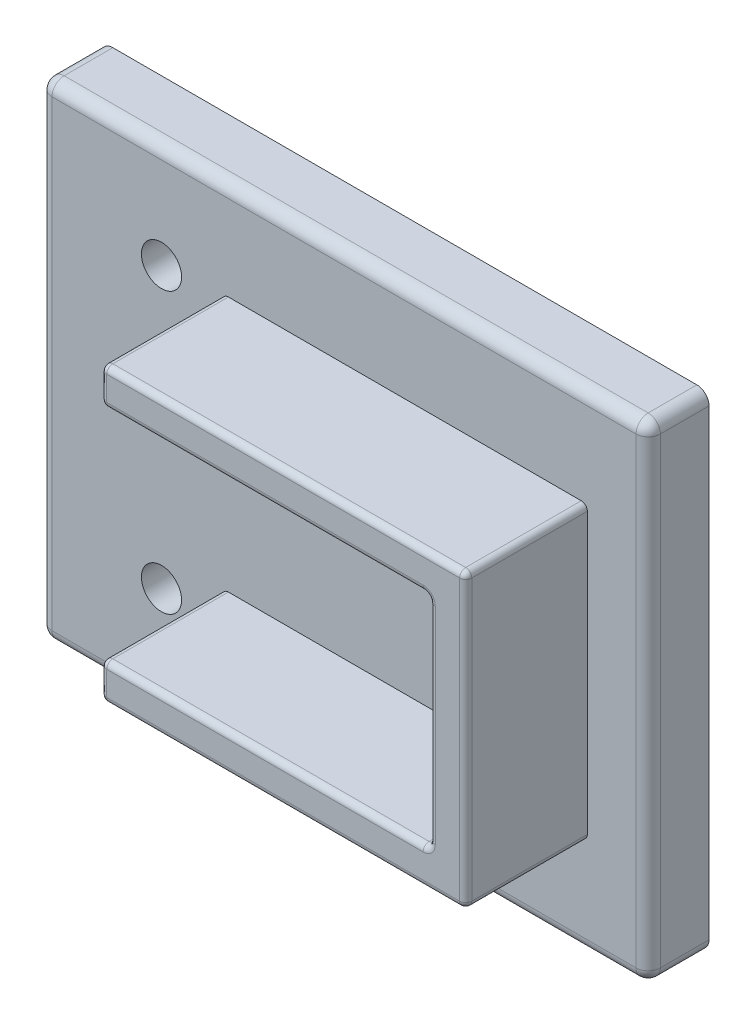
SolidWorks part; units mm, degrees
ref_plane "前视基准面" through (0, 0, 0) normal (0, 0, 1) x (1, 0, 0)
ref_plane "上视基准面" through (0, 0, 0) normal (0, 1, 0) x (1, 0, 0)
ref_plane "右视基准面" through (0, 0, 0) normal (1, 0, 0) x (0, 0, -1)
other "Configuration Table"
sketch "草图2" plane through (0, 0, 0) normal (0, 0, 1) x (1, 0, 0)
  line L1 (78, 30) -> (28, 30)
  line L2 (78, 30) -> (78, -10)
  line L3 (78, -10) -> (28, -10)
  line L4 (28, 30) -> (28, -10)
  line L5 (88, 10) -> (-32, 10) construction
  line L6 (-32, -19) -> (-32, 39) construction
  dimension "D1" = 40
  dimension "D2" = 50
extrude "凸台-拉伸1" add sketch "草图2" along normal blind 5
sketch "草图5" plane through (0, -10, 0) normal (0, -1, 0) x (1, 0, 0)
  line L0 (73, 5) -> (73, 15)
  line L1 (28, 5) -> (78, 5) construction
  line L2 (73, 15) -> (43, 15)
  line L3 (43, 15) -> (43, 5)
  line L4 (43, 5) -> (73, 5)
  line L5 (78, 5) -> (78, 0) construction
  dimension "D1" = 30
  dimension "D2" = 10
  dimension "D3" = 90
  dimension "D4" = 5
extrude "凸台-拉伸2" add sketch "草图5" against normal blind 3 from offset 8 offset against normal yes
sketch "草图6" plane through (0, 30, 0) normal (0, 1, 0) x (1, 0, 0)
  line L4 (73, -15) -> (73, -5)
  line L5 (43, -15) -> (73, -15)
  line L6 (43, -5) -> (43, -15)
  line L7 (73, -5) -> (43, -5)
  line L8 (73, -15) -> (73, -5)
  line L9 (43, -15) -> (73, -15)
  line L10 (43, -5) -> (43, -15)
  line L11 (73, -5) -> (43, -5)
  dimension "D1" = 0
extrude "凸台-拉伸3" add sketch "草图6" against normal blind 3 from offset 8 offset against normal yes
sketch "草图7" plane through (0, 0, 0) normal (0, 0, -1) x (-1, 0, 0)
  circle A4 centre (-63, 10) radius 1.65
  circle A5 centre (-38, -1.5) radius 1.65
  circle A6 centre (-38, 21.5) radius 1.65
  dimension "D1" = 3.3
extrude "切除-拉伸1" cut sketch "草图7" against normal up to next
fillet "圆角3" radius 1 8 edges at (53, -10, 5) (28, 10, 5) (53, 30, 5) (78, 10, 5) (28, -10, 2.5) (28, 30, 2.5) (78, 30, 2.5) (78, -10, 2.5)
sketch "草图8" plane through (73, 0, 0) normal (1, 0, 0) x (0, 0, -1)
  line L1 (-15, 19) -> (-5, 19)
  line L2 (-15, 19) -> (-15, -2)
  line L3 (-15, -2) -> (-5, -2)
  line L4 (-5, 19) -> (-5, -2)
extrude "凸台-拉伸4" add sketch "草图8" against normal blind 3
fillet "圆角4" radius 0.5 16 edges at (56.5, 19, 15) (43, 20.5, 15) (58, 22, 15) (73, 10, 15) (58, -2, 15) (43, -0.5, 15) (56.5, 1, 15) (70, 10, 15) (70, 1, 10) (43, 1, 10) (43, -2, 10) (73, 22, 10) (43, 22, 10) (43, 19, 10) (70, 19, 10) (73, -2, 10)
